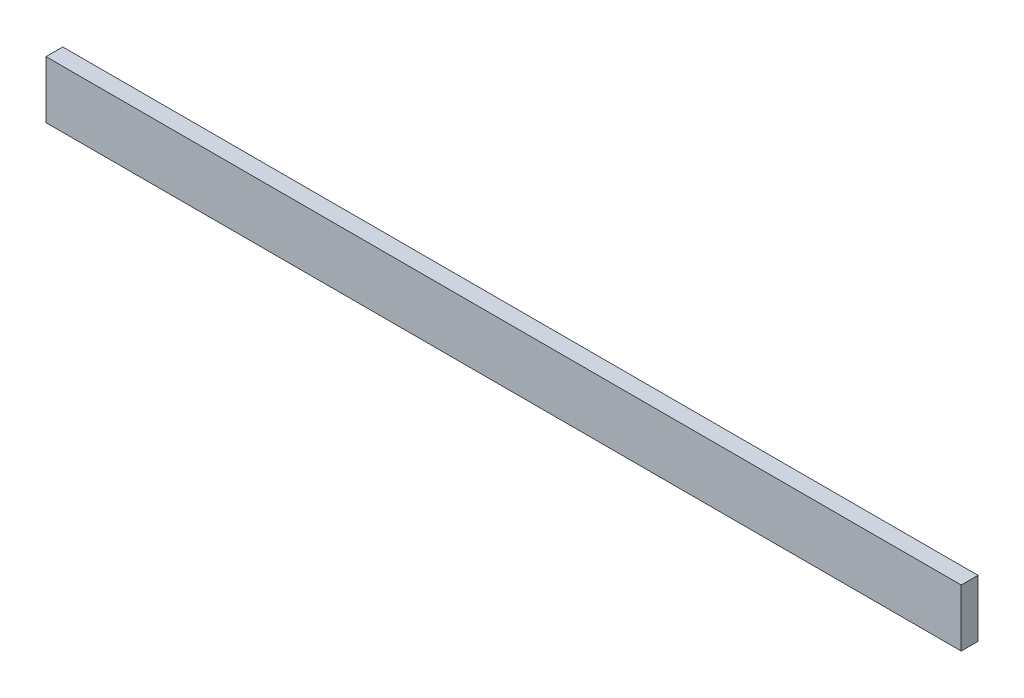
SolidWorks part; units mm, degrees
material "Silicon Rubber"
ref_plane "Front Plane" through (0, 0, 0) normal (0, 0, 1) x (1, 0, 0)
ref_plane "Top Plane" through (0, 0, 0) normal (0, 1, 0) x (1, 0, 0)
ref_plane "Right Plane" through (0, 0, 0) normal (1, 0, 0) x (0, 0, -1)
sketch "Sketch1" plane through (0, 0, 0) normal (0, 0, 1) x (1, 0, 0)
  line L1 (-152.4, -9.525) -> (152.4, -9.525)
  line L2 (-152.4, -9.525) -> (-152.4, 9.525)
  line L3 (-152.4, 9.525) -> (152.4, 9.525)
  line L4 (152.4, -9.525) -> (152.4, 9.525)
  line L5 (-152.4, -9.525) -> (152.4, 9.525) construction
  line L6 (-152.4, 9.525) -> (152.4, -9.525) construction
  point P0 (0, 0)
  dimension "D1" = 19.05
  dimension "D2" = 304.8
extrude "Boss-Extrude1" add sketch "Sketch1" along normal blind 5.588
